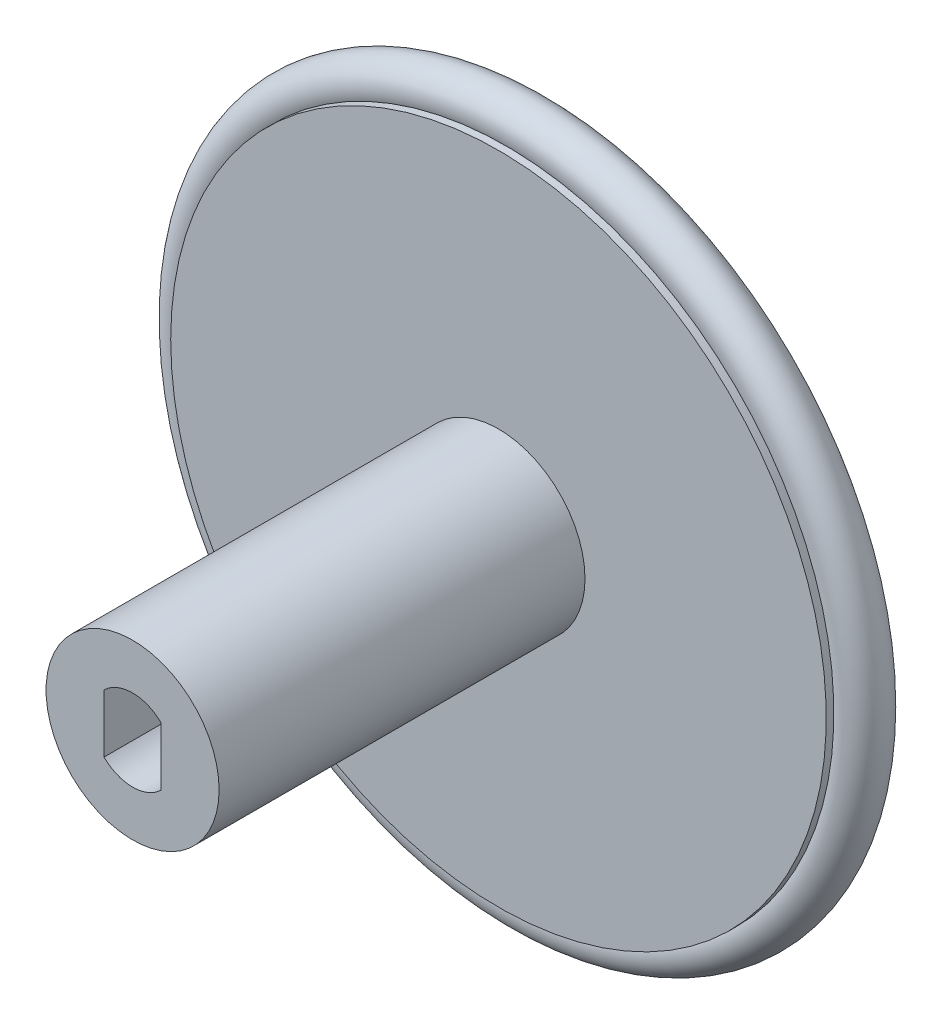
SolidWorks part; units mm, degrees
ref_plane "Alzado" through (0, 0, 0) normal (0, 0, 1) x (1, 0, 0)
ref_plane "Planta" through (0, 0, 0) normal (0, 1, 0) x (1, 0, 0)
ref_plane "Vista lateral" through (0, 0, 0) normal (1, 0, 0) x (0, 0, -1)
sketch "Croquis1" plane through (0, 0, 0) normal (1, 0, 0) x (0, 0, -1)
  line L0 (6.2271, 0) -> (-6.2271, 0) construction
  line L1 (0, 21.5) -> (0, -21.5) construction
  line L2 (-1.9, 0) -> (-1.9, 21.5)
  line L3 (-1.9, 21.5) -> (-1.4, 21.5)
  line L4 (-1.4, 21.5) -> (-0.5, 19.0002)
  line L5 (-0.5, 19.0002) -> (0.5, 19.0002)
  line L6 (1.4, 21.5) -> (0.5, 19.0002)
  line L7 (1.9, 21.5) -> (1.4, 21.5)
  line L8 (1.9, 0) -> (1.9, 21.5)
  line L9 (-1.9, 0) -> (1.9, 0)
  point P4 (0, 0)
  point P8 (0, 0)
  point P18 (0, 19.0002)
  dimension "D1" = 43
  dimension "D2" = 3.8
  dimension "D3" = 19.8
  dimension "D4" = 1
  dimension "D5" = 0.5
  dimension "D6" = 2.6569
revolve "Revolución1" add sketch "Croquis1" angle 360 about L0
sketch "Croquis3" plane through (0, 0, 1.9) normal (0, 0, 1) x (1, 0, 0)
  line L1 (-1.875, 1.9079) -> (1.875, 1.9079) construction
  line L2 (-1.875, 1.9079) -> (-1.875, -1.9079)
  line L3 (-1.875, -1.9079) -> (1.875, -1.9079) construction
  line L4 (1.875, 1.9079) -> (1.875, -1.9079)
  line L5 (-1.875, 1.9079) -> (1.875, -1.9079) construction
  line L6 (-1.875, -1.9079) -> (1.875, 1.9079) construction
  circle A0 centre (0, 0) radius 2.675 construction
  arc A1 (-1.875, 1.9079) -> (1.875, 1.9079) centre (0, 0) cw
  arc A2 (-1.875, -1.9079) -> (1.875, -1.9079) centre (0, 0) ccw
  circle A3 centre (0, 0) radius 5.675
  dimension "D1" = 5.35
  dimension "D4" = 11.35
  dimension "D2" = 3.75
  dimension "D3" = 3
extrude "Saliente-Extruir2" add sketch "Croquis3" along normal blind 24
sketch "Croquis4" plane through (0, 0, 25.9) normal (0, 0, 1) x (1, 0, 0)
  line L2 (-1.875, 1.9079) -> (-1.875, -1.9079)
  line L3 (1.875, -1.9079) -> (1.875, 1.9079)
  line L4 (-1.875, 1.9079) -> (-1.875, -1.9079)
  line L5 (1.875, -1.9079) -> (1.875, 1.9079)
  arc A2 (-1.875, -1.9079) -> (1.875, -1.9079) centre (0, 0) ccw
  arc A3 (1.875, 1.9079) -> (-1.875, 1.9079) centre (0, 0) ccw
  arc A4 (-1.875, -1.9079) -> (1.875, -1.9079) centre (0, 0) ccw
  arc A5 (1.875, 1.9079) -> (-1.875, 1.9079) centre (0, 0) ccw
  dimension "D1" = 0
extrude "Saliente-Extruir3" add sketch "Croquis4" against normal up to next from offset 5 offset against normal yes
sketch "Croquis5" plane through (0, 0, 0) normal (1, 0, 0) x (0, 0, -1)
  line L0 (-0.5, 19.0002) -> (-1.4, 21.5) construction
  line L1 (-9.0932, 0) -> (9.0932, 0) construction
  circle A0 centre (0, 22.0396) radius 1.5
  point P9 (0, 0)
  dimension "D1" = 3
revolve "Revolución2" add sketch "Croquis5" angle 360 about L1
